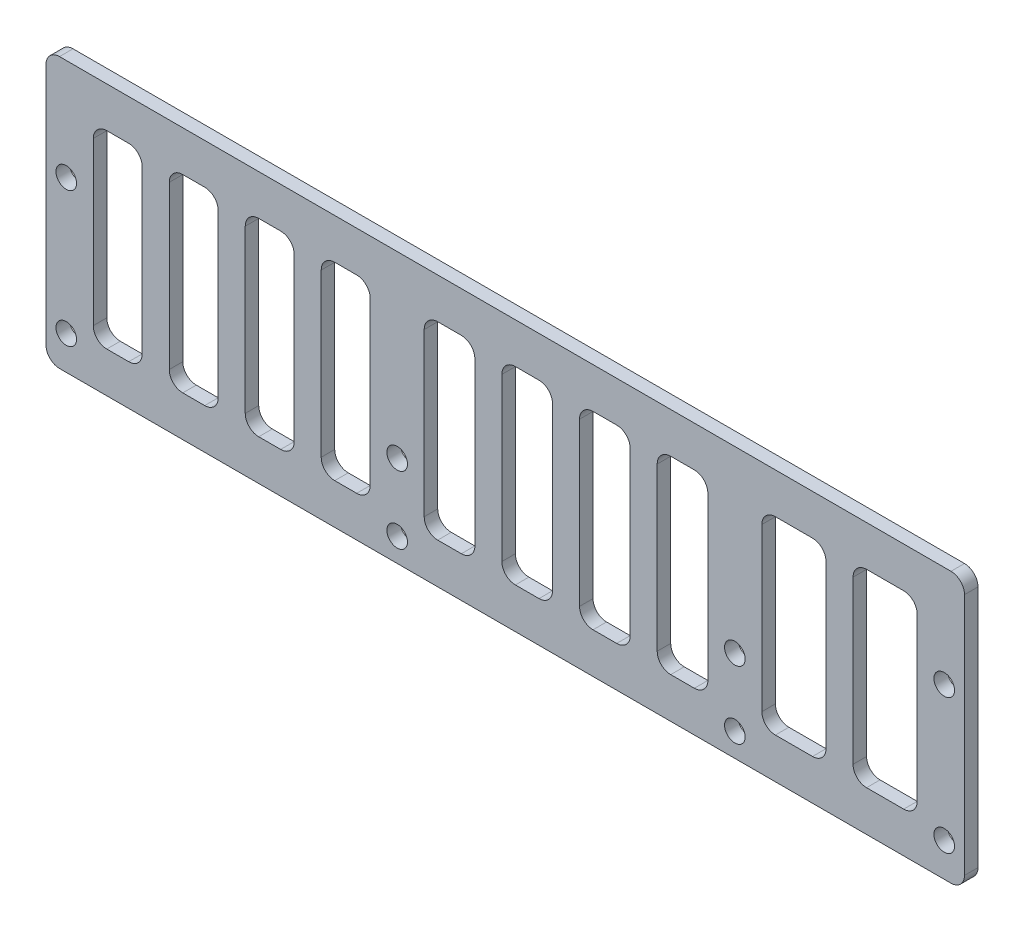
SolidWorks part; units mm, degrees
material "Thornel Mat VMA"
ref_plane "前视基准面" through (0, 0, 0) normal (0, 0, 1) x (1, 0, 0)
ref_plane "上视基准面" through (0, 0, 0) normal (0, 1, 0) x (1, 0, 0)
ref_plane "右视基准面" through (0, 0, 0) normal (1, 0, 0) x (0, 0, -1)
other "Configuration Table"
sketch "草图1" plane through (0, 0, 0) normal (0, 0, 1) x (1, 0, 0)
  line L1 (-68, -20) -> (68, -20)
  line L2 (-68, -20) -> (-68, 20)
  line L3 (-68, 20) -> (68, 20)
  line L4 (68, -20) -> (68, 20)
  line L5 (-68, -20) -> (68, 20) construction
  line L6 (-68, 20) -> (68, -20) construction
  point P0 (0, 0)
  dimension "D1" = 136
  dimension "D2" = 40
extrude "凸台-拉伸1" add sketch "草图1" along normal blind 2
sketch "草图2" plane through (0, 0, 0) normal (0, 0, -1) x (-1, 0, 0)
  circle A0 centre (16, -16.5) radius 2 construction
  circle A1 centre (-34, -16.5) radius 2 construction
  circle A2 centre (-34, -6.5) radius 2 construction
  circle A3 centre (16, -6.5) radius 2 construction
  circle A4 centre (16, -16.5) radius 2 construction
  circle A5 centre (-34, -16.5) radius 2 construction
  circle A6 centre (-34, -6.5) radius 2 construction
  circle A7 centre (16, -6.5) radius 2 construction
  circle A8 centre (-34, -6.5) radius 1.525
  circle A9 centre (-34, -16.5) radius 1.525
  circle A10 centre (16, -6.5) radius 1.525
  circle A11 centre (16, -16.5) radius 1.525
  dimension "D1" = 3.05
extrude "切除-拉伸1" cut sketch "草图2" against normal blind 2
sketch "草图3" plane through (0, 0, 0) normal (0, 0, -1) x (-1, 0, 0)
  line L0 (0, 0) -> (0, 29.6687) construction
  circle A0 centre (65, 5) radius 1.25 construction
  circle A1 centre (65, -15) radius 1.25 construction
  circle A2 centre (65, 5) radius 1.25 construction
  circle A3 centre (65, -15) radius 1.25 construction
  circle A4 centre (65, -15) radius 1.525
  circle A5 centre (65, 5) radius 1.525
  circle A6 centre (-65, -15) radius 1.25 construction
  circle A7 centre (-65, 5) radius 1.25 construction
  circle A8 centre (-65, 5) radius 1.525
  circle A9 centre (-65, -15) radius 1.525
  dimension "D1" = 3.05
extrude "切除-拉伸2" cut sketch "草图3" against normal blind 22
sketch "草图4" plane through (0, 0, 2) normal (0, 0, 1) x (1, 0, 0)
  line L0 (-68, -20) -> (68, -20) construction
  line L1 (-61, 14) -> (-20, 14)
  line L2 (-61, 14) -> (-61, -14)
  line L3 (-61, -14) -> (-20, -14)
  line L4 (-20, 14) -> (-20, -14)
  line L5 (68, 20) -> (-68, 20) construction
  line L6 (-40.5, 14) -> (-40.5, -14) construction
  line L7 (-42.5, 14) -> (-42.5, -14)
  line L8 (-38.5, 14) -> (-38.5, -14)
  circle A0 centre (-16, -6.5) radius 1.525 construction
  circle A1 centre (-65, 5) radius 1.525 construction
  arc A2 (-42.5, 14) -> (-38.5, 14) centre (-40.5, 14) cw
  arc A3 (-42.5, -14) -> (-38.5, -14) centre (-40.5, -14) ccw
  dimension "D1" = 6
  dimension "D2" = 6
  dimension "D3" = 4
  dimension "D4" = 4
  dimension "D5" = 2
  dimension "D6" = 2
extrude "切除-拉伸3" cut sketch "草图4" against normal blind 22 contours L7 L1 L2 L3 | L1 L8 L3 L4
sketch "草图5" plane through (0, 0, 2) normal (0, 0, 1) x (1, 0, 0)
  line L0 (-51.75, 14) -> (-51.75, -14) construction
  line L1 (-42.5, 14) -> (-61, 14) construction
  line L2 (-42.5, -14) -> (-61, -14) construction
  line L3 (-29.25, 14) -> (-29.25, -14) construction
  line L4 (-20, 14) -> (-38.5, 14) construction
  line L5 (-20, -14) -> (-38.5, -14) construction
  line L6 (-53.75, 14) -> (-53.75, -14)
  line L7 (-31.25, 14) -> (-31.25, -14)
  line L8 (-49.75, 14) -> (-49.75, -14)
  line L9 (-27.25, 14) -> (-27.25, -14)
  arc A0 (-53.75, 14) -> (-49.75, 14) centre (-51.75, 14) cw
  arc A1 (-53.75, -14) -> (-49.75, -14) centre (-51.75, -14) ccw
  arc A2 (-31.25, 14) -> (-27.25, 14) centre (-29.25, 14) cw
  arc A3 (-31.25, -14) -> (-27.25, -14) centre (-29.25, -14) ccw
  dimension "D1" = 2
  dimension "D2" = 2
extrude "凸台-拉伸2" add sketch "草图5" against normal up to surface (2 mm away) up to face at (66.525, -15, 0)
sketch "草图6" plane through (0, 0, 2) normal (0, 0, 1) x (1, 0, 0)
  line L0 (-38.5, -14) -> (-31.25, -14) construction
  line L1 (38, 14) -> (61, 14)
  line L2 (38, 14) -> (38, -14)
  line L3 (38, -14) -> (61, -14)
  line L4 (61, 14) -> (61, -14)
  line L5 (-27.25, 14) -> (-20, 14) construction
  line L6 (49.5, 14) -> (49.5, -14) construction
  line L7 (47.5, 14) -> (47.5, -14)
  line L8 (51.5, 14) -> (51.5, -14)
  circle A0 centre (65, 5) radius 1.525 construction
  circle A1 centre (34, -6.5) radius 1.525 construction
  arc A2 (47.5, 14) -> (51.5, 14) centre (49.5, 14) cw
  arc A3 (47.5, -14) -> (51.5, -14) centre (49.5, -14) ccw
  dimension "D1" = 4
  dimension "D2" = 4
  dimension "D3" = 2
  dimension "D4" = 2
extrude "切除-拉伸4" cut sketch "草图6" against normal up to surface (2 mm away) contours L7 L1 L2 L3 | L1 L8 L3 L4 up to face at (-34.875, 0, 0)
fillet "圆角1" radius 2 24 edges at (38, -14, 1) (38, 14, 1) (47.5, 14, 1) (47.5, -14, 1) (-49.75, 14, 1) (-42.5, 14, 1) (-42.5, -14, 1) (-49.75, -14, 1) (-61, -14, 1) (-61, 14, 1) (-53.75, 14, 1) (-53.75, -14, 1) (-27.25, 14, 1) (-20, 14, 1) (-38.5, -14, 1) (-38.5, 14, 1) (-31.25, 14, 1) (-31.25, -14, 1) (51.5, 14, 1) (61, 14, 1) (61, -14, 1) (51.5, -14, 1) (-27.25, -14, 1) (-20, -14, 1)
sketch "草图7" plane through (0, 0, 2) normal (0, 0, 1) x (1, 0, 0)
  line L0 (40, 14) -> (45.5, 14) construction
  line L1 (-12, -14) -> (30, -14)
  line L2 (-12, -14) -> (-12, 14)
  line L3 (-12, 14) -> (30, 14)
  line L4 (30, -14) -> (30, 14)
  line L5 (40, -14) -> (45.5, -14) construction
  line L6 (9, 14) -> (9, -14) construction
  line L7 (7, 14) -> (7, -14)
  line L8 (11, 14) -> (11, -14)
  circle A0 centre (34, -6.5) radius 1.525 construction
  circle A1 centre (-16, -6.5) radius 1.525 construction
  arc A2 (7, 14) -> (11, 14) centre (9, 14) cw
  arc A3 (7, -14) -> (11, -14) centre (9, -14) ccw
  dimension "D1" = 4
  dimension "D2" = 4
  dimension "D3" = 2
  dimension "D4" = 2
extrude "切除-拉伸5" cut sketch "草图7" against normal up to surface (2 mm away) contours L7 L3 L2 L1 | L3 L8 L1 L4 up to face at (56.25, 0, 0)
sketch "草图8" plane through (0, 0, 2) normal (0, 0, 1) x (1, 0, 0)
  line L0 (-2.5, 14) -> (-2.5, -14) construction
  line L1 (-12, 14) -> (7, 14) construction
  line L2 (-12, -14) -> (7, -14) construction
  line L3 (20.5, 14) -> (20.5, -14) construction
  line L4 (11, 14) -> (30, 14) construction
  line L5 (11, -14) -> (30, -14) construction
  line L6 (-4.5, 14) -> (-4.5, -14)
  line L7 (18.5, 14) -> (18.5, -14)
  line L8 (-0.5, 14) -> (-0.5, -14)
  line L9 (22.5, 14) -> (22.5, -14)
  arc A0 (-4.5, 14) -> (-0.5, 14) centre (-2.5, 14) cw
  arc A1 (-4.5, -14) -> (-0.5, -14) centre (-2.5, -14) ccw
  arc A2 (18.5, 14) -> (22.5, 14) centre (20.5, 14) cw
  arc A3 (18.5, -14) -> (22.5, -14) centre (20.5, -14) ccw
  dimension "D1" = 2
  dimension "D2" = 2
extrude "凸台-拉伸3" add sketch "草图8" against normal up to surface (2 mm away) up to face at (20.5, 0, 0)
fillet "圆角2" radius 2 16 edges at (-0.5, 14, 1) (7, 14, 1) (7, -14, 1) (-0.5, -14, 1) (-12, -14, 1) (-12, 14, 1) (-4.5, 14, 1) (-4.5, -14, 1) (22.5, 14, 1) (22.5, -14, 1) (11, -14, 1) (11, 14, 1) (18.5, 14, 1) (18.5, -14, 1) (30, 14, 1) (30, -14, 1)
fillet "圆角3" radius 2 4 edges at (68, -20, 1) (68, 20, 1) (-68, -20, 1) (-68, 20, 1)
